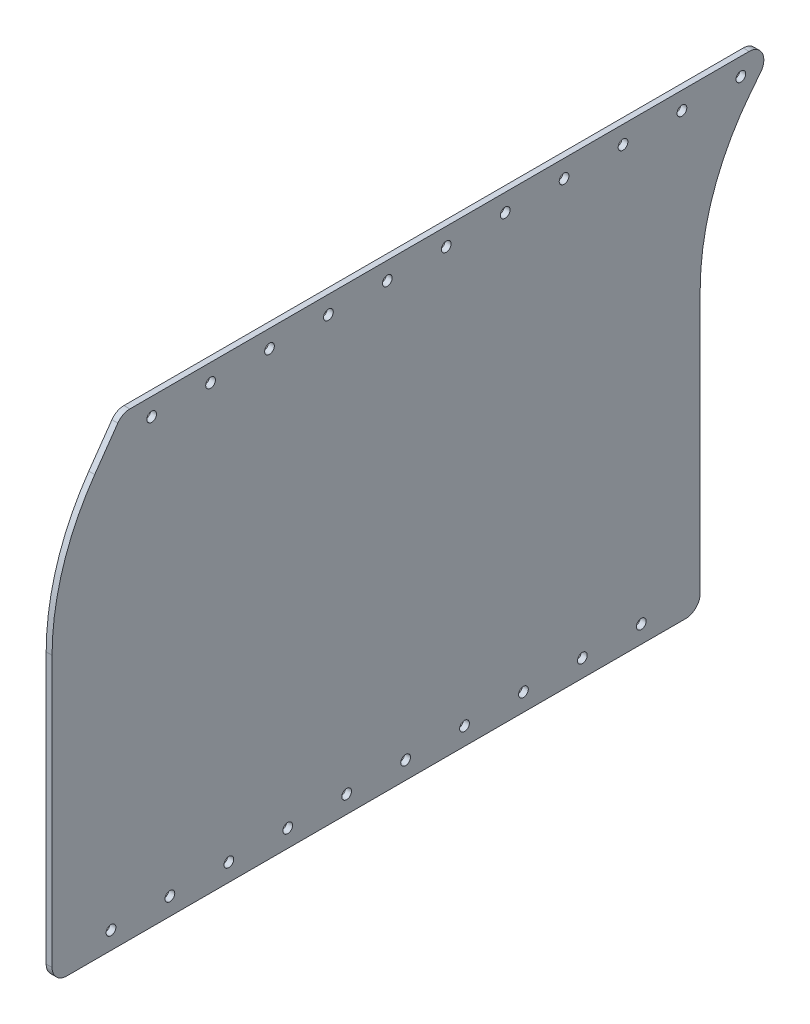
SolidWorks part; units mm, degrees
ref_plane "Front Plane" through (0, 0, 0) normal (0, 0, 1) x (1, 0, 0)
ref_plane "Top Plane" through (0, 0, 0) normal (0, 1, 0) x (1, 0, 0)
ref_plane "Right Plane" through (0, 0, 0) normal (1, 0, 0) x (0, 0, -1)
sketch "Sketch1" plane through (0, 0, 0) normal (1, 0, 0) x (0, 0, -1)
  line L0 (-138.9484, -3.0511) -> (140.4516, -3.0511) construction
  line L1 (-138.9484, -3.0511) -> (140.4516, -3.0511)
  line L2 (-138.9484, -3.0511) -> (-138.9484, 151.8969)
  line L4 (140.4516, -3.0511) -> (140.4516, 151.8969)
  line L5 (-138.9484, -3.0511) -> (-138.9484, 10.9189) construction
  line L6 (140.4516, 10.9189) -> (140.4516, -3.0511) construction
  line L7 (-138.9484, 151.8969) -> (-108.719, 195.0689)
  line L9 (140.4516, 151.8969) -> (174.674, 195.0689)
  line L10 (174.674, 195.0689) -> (-108.719, 195.0689)
  circle A0 centre (-113.5484, 4.5689) radius 2.0955 construction
  circle A1 centre (-113.5484, 4.5689) radius 2.0955
  circle A2 centre (-88.1484, 4.5689) radius 2.0955
  circle A3 centre (-62.7484, 4.5689) radius 2.0955
  circle A4 centre (-37.3484, 4.5689) radius 2.0955
  circle A5 centre (-11.9484, 4.5689) radius 2.0955
  circle A6 centre (13.4516, 4.5689) radius 2.0955
  circle A7 centre (38.8516, 4.5689) radius 2.0955
  circle A8 centre (64.2516, 4.5689) radius 2.0955
  circle A9 centre (89.6516, 4.5689) radius 2.0955
  circle A10 centre (115.0516, 4.5689) radius 2.0955
  circle A11 centre (-96.019, 187.4489) radius 2.0955 construction
  circle A12 centre (-96.019, 187.4489) radius 2.0955
  circle A13 centre (-70.619, 187.4489) radius 2.0955
  circle A14 centre (-45.219, 187.4489) radius 2.0955
  circle A15 centre (-19.819, 187.4489) radius 2.0955
  circle A16 centre (5.581, 187.4489) radius 2.0955
  circle A17 centre (30.981, 187.4489) radius 2.0955
  circle A18 centre (56.381, 187.4489) radius 2.0955
  circle A19 centre (81.781, 187.4489) radius 2.0955
  circle A20 centre (107.181, 187.4489) radius 2.0955
  circle A21 centre (132.581, 187.4489) radius 2.0955
  circle A22 centre (157.981, 187.4489) radius 2.0955
  point P0 (0, 0)
  dimension "D1" = 145
  dimension "D2" = 10
  dimension "D3" = 11
extrude "Boss-Extrude1" add sketch "Sketch1" along normal mid plane 2.54
fillet "Fillet1" radius 6.35 4 edges at (0, -3.0511, -140.4516) (0, -3.0511, 138.9484) (0, 195.0689, 108.719) (0, 195.0689, -174.674)
fillet "Fillet2" radius 101.6 2 edges at (0, 151.8969, -140.4516) (0, 151.8969, 138.9484)
